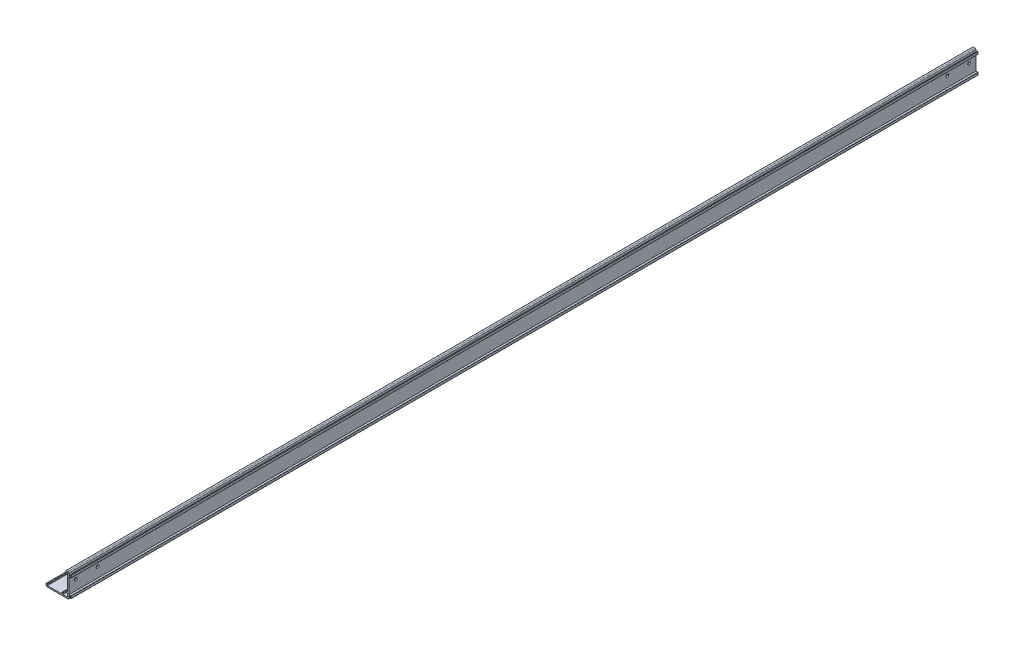
SolidWorks part; units mm, degrees
ref_plane "Front Plane" through (0, 0, 0) normal (0, 0, 1) x (1, 0, 0)
ref_plane "Top Plane" through (0, 0, 0) normal (0, 1, 0) x (1, 0, 0)
ref_plane "Right Plane" through (0, 0, 0) normal (1, 0, 0) x (0, 0, -1)
sketch "Main" plane through (0, 0, 0) normal (0, 1, 0) x (1, 0, 0)
  line L1 (-23.368, -844.55) -> (23.368, -844.55)
  line L2 (-23.368, -844.55) -> (-23.368, 844.55)
  line L3 (-23.368, 844.55) -> (23.368, 844.55)
  line L4 (23.368, -844.55) -> (23.368, 844.55)
  line L5 (-23.368, -844.55) -> (23.368, 844.55) construction
  line L6 (-23.368, 844.55) -> (23.368, -844.55) construction
  point P0 (0, 0)
  dimension "D1" = 1689.1
  dimension "D2" = 46.736
extrude "Extrude-Main" add sketch "Main" along normal blind 44.45
sketch "Main Cut" plane through (0, 0, 844.55) normal (0, 0, 1) x (1, 0, 0)
  line L1 (-23.368, 44.45) -> (13.97, 44.45)
  line L2 (-23.368, 44.45) -> (-23.368, 5.08)
  line L3 (-23.368, 5.08) -> (13.97, 5.08)
  line L4 (13.97, 44.45) -> (13.97, 5.08)
  dimension "D1" = 39.37
  dimension "D2" = 37.338
extrude "Cut-Main" cut sketch "Main Cut" against normal through all
sketch "Bottom Left" plane through (0, 0, 844.55) normal (0, 0, 1) x (1, 0, 0)
  line L0 (-23.368, 5.08) -> (13.97, 5.08) construction
  line L1 (-20.828, 5.08) -> (5.842, 5.08)
  line L2 (-20.828, 5.08) -> (-20.828, 2.413)
  line L3 (-20.828, 2.413) -> (5.842, 2.413)
  line L4 (5.842, 5.08) -> (5.842, 2.413)
  line L5 (-23.368, 5.08) -> (-23.368, 0) construction
  line L6 (-23.368, 0) -> (23.368, 0) construction
  dimension "D1" = 2.54
  dimension "D2" = 26.67
  dimension "D3" = 2.413
extrude "Cut-Bottom Left" cut sketch "Bottom Left" against normal through all
sketch "Bottom Right" plane through (0, 0, 844.55) normal (0, 0, 1) x (1, 0, 0)
  line L0 (5.842, 5.08) -> (13.97, 5.08) construction
  line L1 (7.874, 5.08) -> (13.97, 5.08)
  line L2 (7.874, 5.08) -> (7.874, 2.413)
  line L3 (7.874, 2.413) -> (13.97, 2.413)
  line L4 (13.97, 5.08) -> (13.97, 2.413)
  line L5 (5.842, 2.413) -> (5.842, 5.08) construction
  line L6 (-23.368, 0) -> (23.368, 0) construction
  line L7 (13.97, 5.08) -> (13.97, 44.45) construction
  dimension "D1" = 2.032
  dimension "D2" = 0
  dimension "D3" = 2.413
extrude "Cut-Bottom Right" cut sketch "Bottom Right" against normal through all
sketch "Left Bottom" plane through (0, 0, 844.55) normal (0, 0, 1) x (1, 0, 0)
  line L7 (13.97, 2.413) -> (17.018, 2.413)
  line L8 (13.97, 2.413) -> (13.97, 9.271)
  line L9 (13.97, 9.271) -> (17.018, 9.271)
  line L10 (17.018, 2.413) -> (17.018, 9.271)
  dimension "D1" = 6.858
  dimension "D2" = 3.048
extrude "Cut-Left Bottom" cut sketch "Left Bottom" against normal through all
sketch "Left Middle" plane through (0, 0, 844.55) normal (0, 0, 1) x (1, 0, 0)
  line L0 (13.97, 9.271) -> (13.97, 44.45) construction
  line L1 (13.97, 11.4902) -> (17.018, 11.4902)
  line L2 (13.97, 11.4902) -> (13.97, 41.9702)
  line L3 (13.97, 41.9702) -> (17.018, 41.9702)
  line L4 (17.018, 11.4902) -> (17.018, 41.9702)
  line L5 (17.018, 9.271) -> (17.018, 2.413) construction
  dimension "D1" = 30.48
  dimension "D2" = 0
extrude "Cut-Left Mid" cut sketch "Left Middle" against normal through all
sketch "Right Middle" plane through (0, 0, 844.55) normal (0, 0, 1) x (1, 0, 0)
  line L0 (23.368, 44.45) -> (23.368, 0) construction
  line L1 (19.431, 7.874) -> (27.305, 7.874)
  line L2 (19.431, 7.874) -> (19.431, 36.576)
  line L3 (19.431, 36.576) -> (27.305, 36.576)
  line L4 (27.305, 7.874) -> (27.305, 36.576)
  line L5 (19.431, 7.874) -> (27.305, 36.576) construction
  line L6 (19.431, 36.576) -> (27.305, 7.874) construction
  line L7 (17.018, 11.4902) -> (17.018, 41.9702) construction
  point P0 (23.368, 22.225)
  dimension "D1" = 28.702
  dimension "D2" = 2.413
extrude "Cut-Right Mid" cut sketch "Right Middle" against normal through all
sketch "Hooks" plane through (0, 0, 844.55) normal (0, 0, 1) x (1, 0, 0)
  line L0 (19.431, 22.225) -> (15.4247, 22.225) construction
  line L1 (19.431, 36.576) -> (19.431, 7.874) construction
  line L2 (15.4247, 22.225) -> (33.1764, 22.225) construction
  line L3 (19.431, 44.45) -> (19.431, 38.1635)
  line L4 (13.97, 44.45) -> (23.368, 44.45) construction
  line L5 (19.431, 38.1635) -> (21.7805, 38.1635)
  line L6 (21.7805, 38.1635) -> (21.7805, 41.402)
  line L7 (21.7805, 41.402) -> (23.368, 41.402)
  line L8 (23.368, 44.45) -> (23.368, 36.576) construction
  line L9 (23.368, 41.402) -> (23.368, 44.45)
  line L10 (23.368, 44.45) -> (19.431, 44.45)
  line L11 (23.368, 36.576) -> (19.431, 36.576) construction
  line L12 (23.368, 3.048) -> (23.368, 0)
  line L13 (21.7805, 3.048) -> (23.368, 3.048)
  line L14 (21.7805, 6.2865) -> (21.7805, 3.048)
  line L15 (19.431, 6.2865) -> (21.7805, 6.2865)
  line L16 (19.431, 0) -> (19.431, 6.2865)
  line L17 (23.368, 0) -> (19.431, 0)
  dimension "D1" = 1.5875
  dimension "D2" = 1.5875
  dimension "D3" = 4.826
extrude "Hook Cut" cut sketch "Hooks" against normal through all
fillet "Fillet3" radius 1.905 3 edges at (19.431, 0, 0) (19.431, 44.45, 0) (-23.368, 0, 0)
fillet "Fillet4" radius 0.508 14 edges at (-23.368, 5.08, 0) (-20.828, 5.08, 0) (13.97, 41.9702, 0) (13.97, 44.45, 0) (13.97, 9.271, 0) (13.97, 11.4902, 0) (5.842, 5.08, 0) (7.874, 5.08, 0) (23.368, 41.402, 0) (23.368, 36.576, 0) (23.368, 7.874, 0) (23.368, 3.048, 0) (21.7805, 3.048, 0) (21.7805, 41.402, 0)
sketch "Center Line" plane through (17.018, 0, 0) normal (-1, 0, 0) x (0, 0, 1)
  line L0 (844.55, 26.7302) -> (-844.55, 26.7302) construction
  line L1 (844.55, 11.4902) -> (844.55, 41.9702) construction
  line L2 (-844.55, 11.4902) -> (-844.55, 41.9702) construction
  line L4 (0, 43.942) -> (0, 0) construction
  line L5 (844.55, 43.942) -> (-844.55, 43.942) construction
  point P6 (831.85, 26.7302)
  point P7 (791.21, 26.7302)
  point P16 (-831.85, 26.7302)
  point P18 (-791.21, 26.7302)
  dimension "D1" = 12.7
  dimension "D2" = 53.34
  dimension "D3" = 12.7
  dimension "D4" = 53.34
hole_wizard "Screw Holes" positions "Center Line" profile "Hole" hole size "#4" standard "ANSI Inch" end condition through all
sketch "Hole" plane through (17.018, 26.7302, -791.21) normal (0, 1, 0) x (0, 0, 1)
  line L0 (0, 0) -> (0, 6.35)
  line L1 (0, 6.35) -> (2.6543, 6.35)
  line L2 (2.6543, 6.35) -> (2.6543, 0)
  line L5 (2.6543, 0) -> (0, 0)
  line L11 (0, -6.35) -> (0, 107.95) construction
  dimension "Thru Hole Dia." = 5.3086
  dimension "Thru Hole Depth" = 6.35
